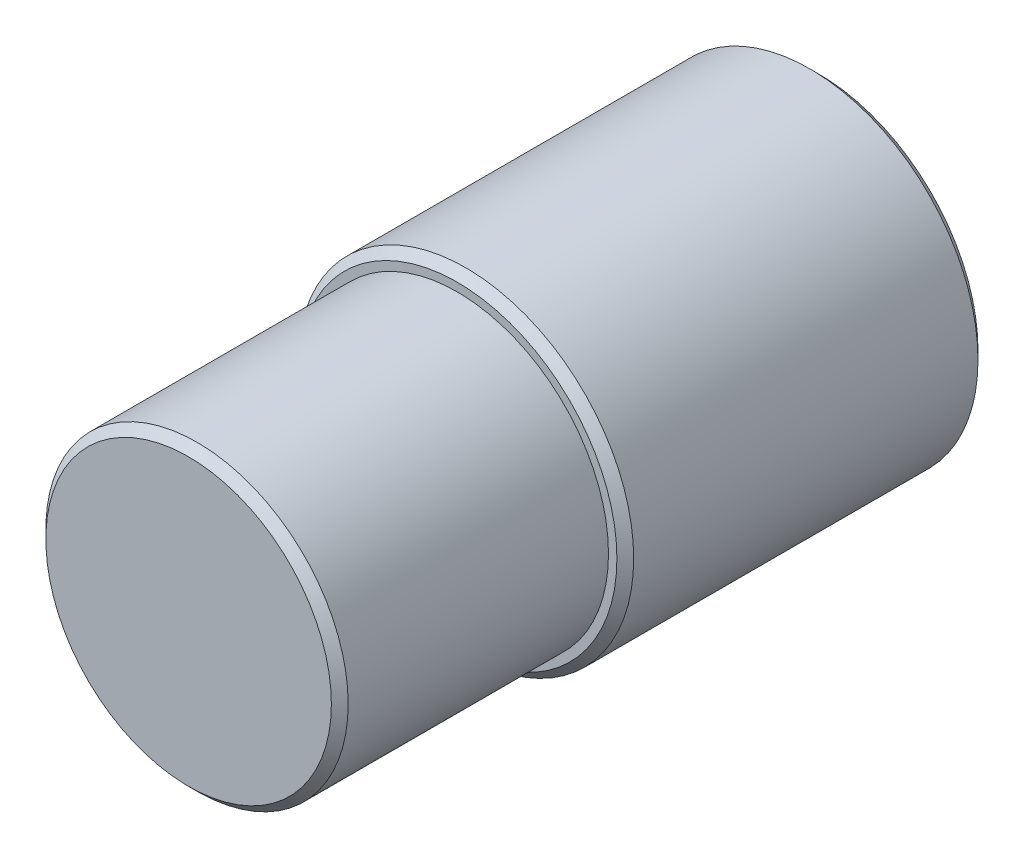
SolidWorks part; units mm, degrees
ref_plane "前视基准面" through (0, 0, 0) normal (0, 0, 1) x (1, 0, 0)
ref_plane "上视基准面" through (0, 0, 0) normal (0, 1, 0) x (1, 0, 0)
ref_plane "右视基准面" through (0, 0, 0) normal (1, 0, 0) x (0, 0, -1)
sketch "草图1" plane through (0, 0, 0) normal (0, 0, 1) x (1, 0, 0)
  circle A0 centre (0, 0) radius 10
  dimension "D1" = 20
extrude "凸台-拉伸1" add sketch "草图1" along normal blind 21.5
sketch "草图2" plane through (0, 0, 21.5) normal (0, 0, 1) x (1, 0, 0)
  circle A0 centre (0, 0) radius 9
  dimension "D1" = 18
extrude "凸台-拉伸2" add sketch "草图2" along normal blind 16
chamfer "倒角1" distance 0.5 angle 45 3 edges at (10, 0, 0) (10, 0, 21.5) (9, 0, 37.5)
